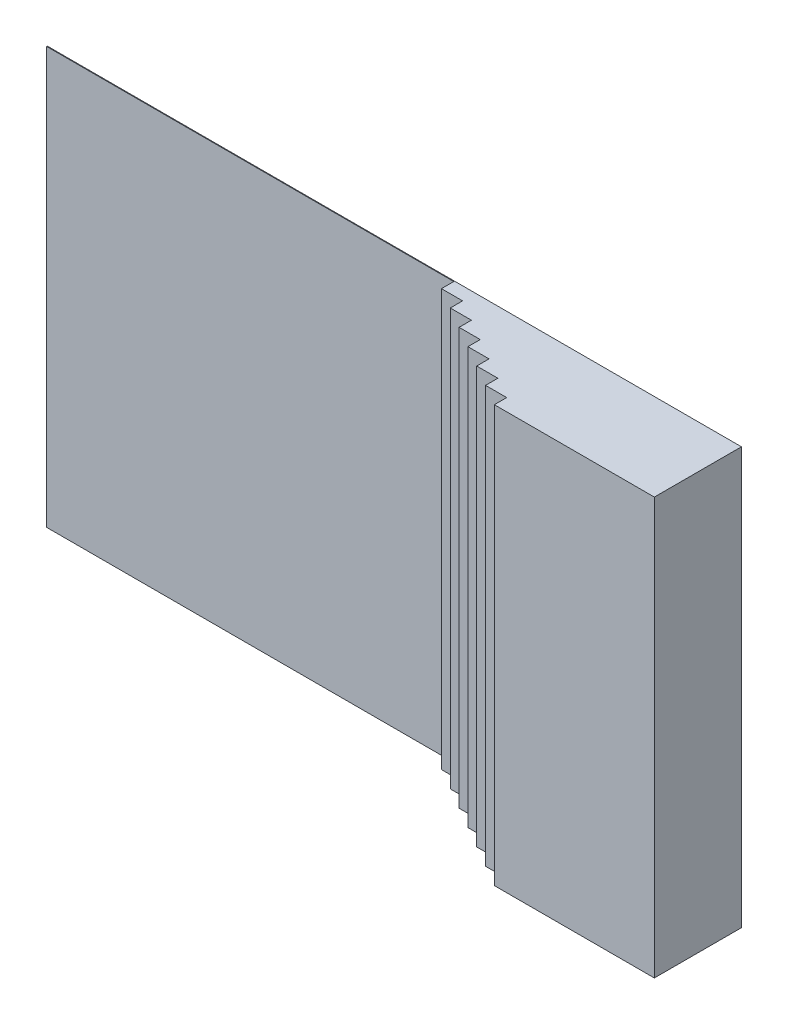
SolidWorks part; units mm, degrees
ref_plane "Front Plane" through (0, 0, 0) normal (0, 0, 1) x (1, 0, 0)
ref_plane "Top Plane" through (0, 0, 0) normal (0, 1, 0) x (1, 0, 0)
ref_plane "Right Plane" through (0, 0, 0) normal (1, 0, 0) x (0, 0, -1)
sketch "Sketch1" plane through (0, 0, 0) normal (0, 0, 1) x (1, 0, 0)
  line L1 (-2500, 3000) -> (7500, 3000)
  line L2 (-2500, 3000) -> (-2500, -3000)
  line L3 (-2500, -3000) -> (7500, -3000)
  line L4 (7500, 3000) -> (7500, -3000)
  dimension "D1" = 6000
  dimension "D2" = 10000
  dimension "D3" = 2500
  dimension "D4" = 3000
extrude "Boss-Extrude1" add sketch "Sketch1" against normal blind 10
sketch "Sketch2" plane through (0, -3000, 0) normal (0, -1, 0) x (1, 0, 0)
  line L0 (3366.4, 0) -> (3366.4, 177.8)
  line L2 (5500, 1244.6) -> (7500, 1244.6)
  line L3 (7500, 1244.6) -> (7500, 0)
  line L22 (3366.4, 177.8) -> (3671.2, 177.8)
  line L24 (3366.4, 0) -> (7500, 0)
  line L25 (3366.4, 0) -> (5500, 1244.6) construction
  line L26 (3671.2, 177.8) -> (3671.2, 355.6)
  line L27 (3671.2, 355.6) -> (3976, 355.6)
  line L28 (3976, 355.6) -> (3976, 533.4)
  line L29 (3976, 533.4) -> (4280.8, 533.4)
  line L30 (4280.8, 533.4) -> (4280.8, 711.2)
  line L31 (4280.8, 711.2) -> (4585.6, 711.2)
  line L32 (4585.6, 711.2) -> (4585.6, 889)
  line L33 (4585.6, 889) -> (4890.4, 889)
  line L34 (4890.4, 889) -> (4890.4, 1066.8)
  line L35 (4890.4, 1066.8) -> (5195.2, 1066.8)
  line L36 (5195.2, 1066.8) -> (5195.2, 1244.6)
  line L37 (5195.2, 1244.6) -> (5500, 1244.6)
  point P0 (0, 0)
  dimension "D2" = 177.8
  dimension "D1" = 2000
  dimension "D4" = 7
extrude "Boss-Extrude2" add sketch "Sketch2" against normal up to surface (6000 mm away) up to face at (2500, 3000, -5)
